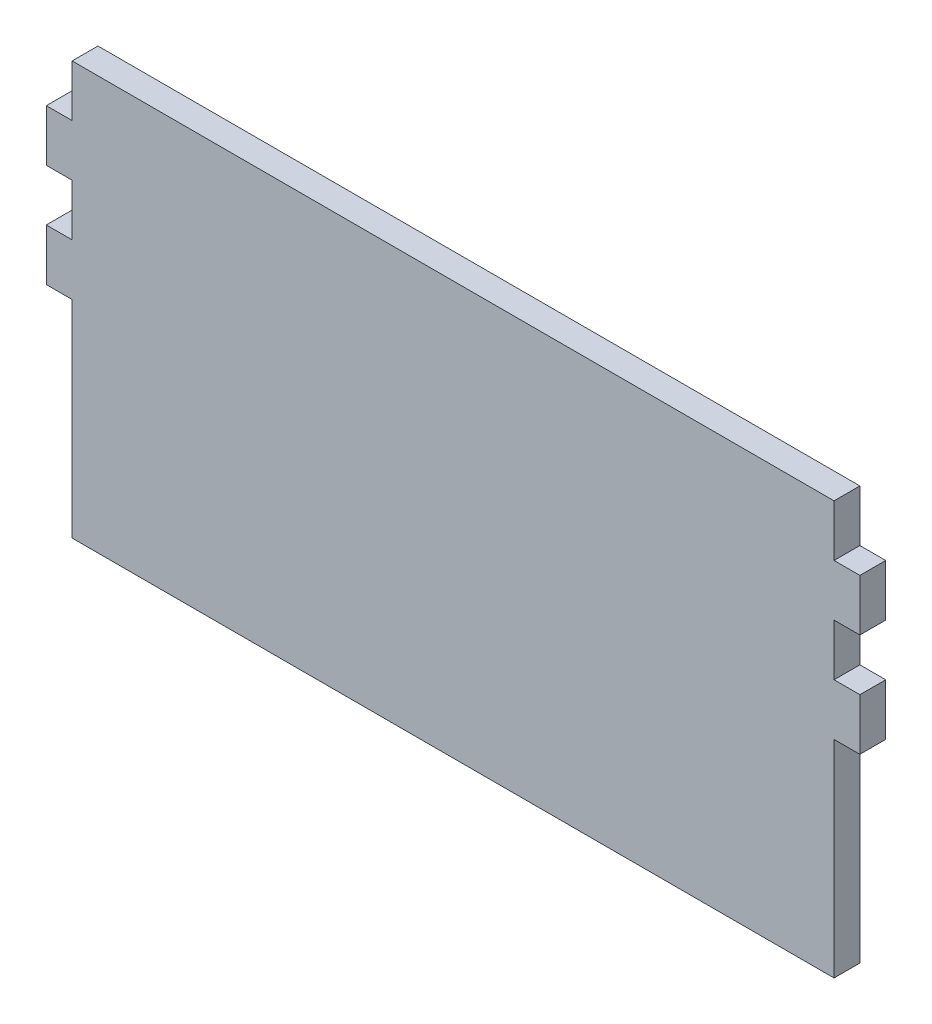
SolidWorks part; units mm, degrees
ref_plane "Front Plane" through (0, 0, 0) normal (0, 0, 1) x (1, 0, 0)
ref_plane "Top Plane" through (0, 0, 0) normal (0, 1, 0) x (1, 0, 0)
ref_plane "Right Plane" through (0, 0, 0) normal (1, 0, 0) x (0, 0, -1)
sketch "Sketch1" plane through (0, 0, 0) normal (0, 0, 1) x (1, 0, 0)
  line L0 (-93.6625, 50.8) -> (-93.6625, 38.1)
  line L1 (-93.6625, -50.8) -> (93.6625, -50.8)
  line L2 (-93.6625, -50.8) -> (-93.6625, 50.8) construction
  line L3 (-93.6625, 50.8) -> (93.6625, 50.8)
  line L4 (93.6625, -50.8) -> (93.6625, 50.8) construction
  line L5 (-93.6625, -50.8) -> (93.6625, 50.8) construction
  line L6 (-93.6625, 50.8) -> (93.6625, -50.8) construction
  line L7 (-93.6625, 38.1) -> (-100.0125, 38.1)
  line L8 (-100.0125, 38.1) -> (-100.0125, 25.4)
  line L9 (-100.0125, 25.4) -> (-93.6625, 25.4)
  line L10 (-93.6625, 25.4) -> (-93.6625, 12.7)
  line L11 (-93.6625, 12.7) -> (-100.0125, 12.7)
  line L12 (-100.0125, 12.7) -> (-100.0125, 0)
  line L13 (-100.0125, 0) -> (-93.6625, 0)
  line L14 (-93.6625, 0) -> (-93.6625, -50.8)
  line L15 (93.6625, 50.8) -> (93.6625, 38.1)
  line L16 (93.6625, 38.1) -> (100.0125, 38.1)
  line L17 (100.0125, 38.1) -> (100.0125, 25.4)
  line L18 (100.0125, 25.4) -> (93.6625, 25.4)
  line L19 (93.6625, 25.4) -> (93.6625, 12.7)
  line L20 (93.6625, 12.7) -> (100.0125, 12.7)
  line L21 (100.0125, 12.7) -> (100.0125, 0)
  line L22 (100.0125, 0) -> (93.6625, 0)
  line L23 (93.6625, 0) -> (93.6625, -50.8)
  point P0 (0, 0)
  dimension "D1" = 101.6
  dimension "D2" = 187.325
  dimension "D3" = 12.7
  dimension "D4" = 6.35
extrude "Boss-Extrude1" add sketch "Sketch1" along normal mid plane 6.35
equation "\"D2@Sketch1\"=8-.5-.125"
